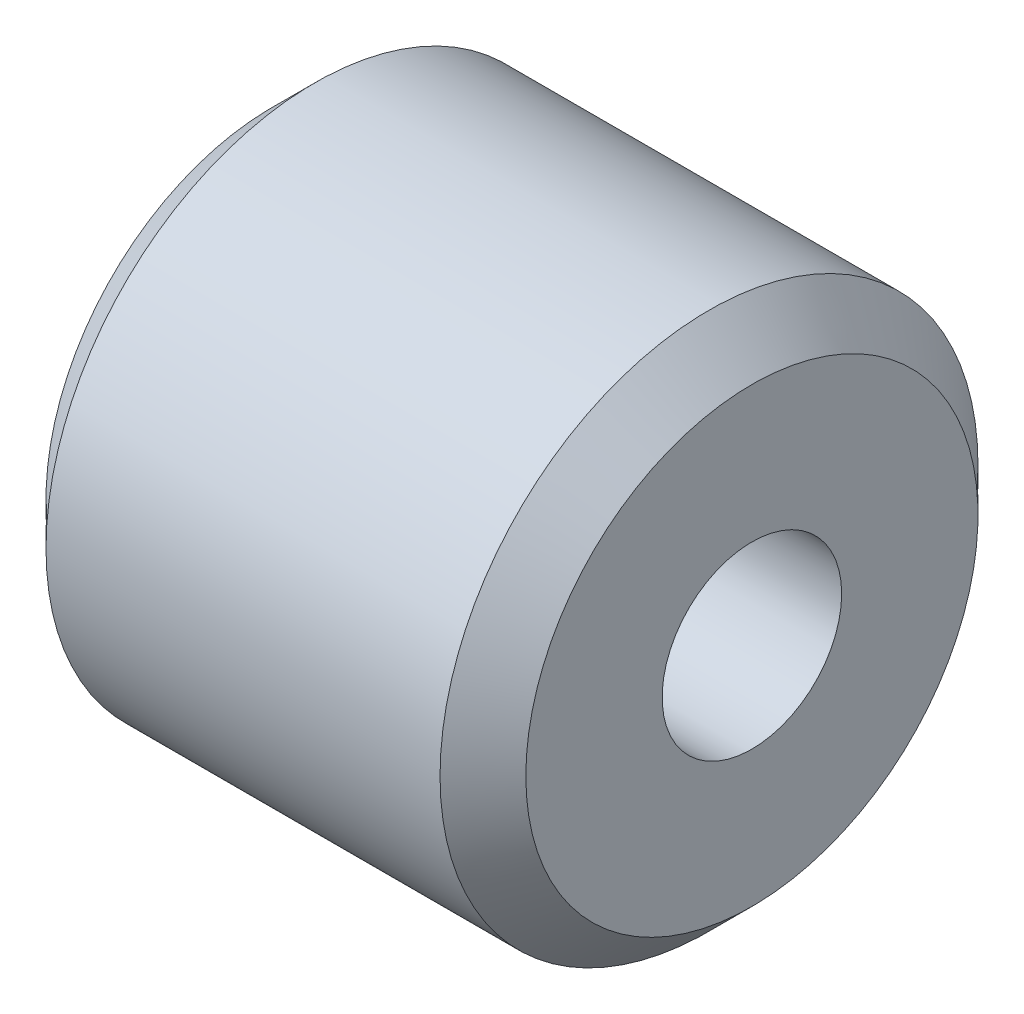
SolidWorks part; units mm, degrees
ref_plane "Front Plane" through (0, 0, 0) normal (0, 0, 1) x (1, 0, 0)
ref_plane "Top Plane" through (0, 0, 0) normal (0, 1, 0) x (1, 0, 0)
ref_plane "Right Plane" through (0, 0, 0) normal (1, 0, 0) x (0, 0, -1)
sketch "Sketch1" plane through (0, 0, 0) normal (1, 0, 0) x (0, 0, -1)
  circle A0 centre (0, 0) radius 1.59
  circle A1 centre (0, 0) radius 4.765
  dimension "D1" = 3.18
  dimension "D2" = 9.53
extrude "Boss-Extrude1" add sketch "Sketch1" along normal mid plane 8.5
chamfer "Chamfer1" distance 0.76 angle 45 2 edges at (4.25, 0, -4.765) (-4.25, 0, -4.765)
